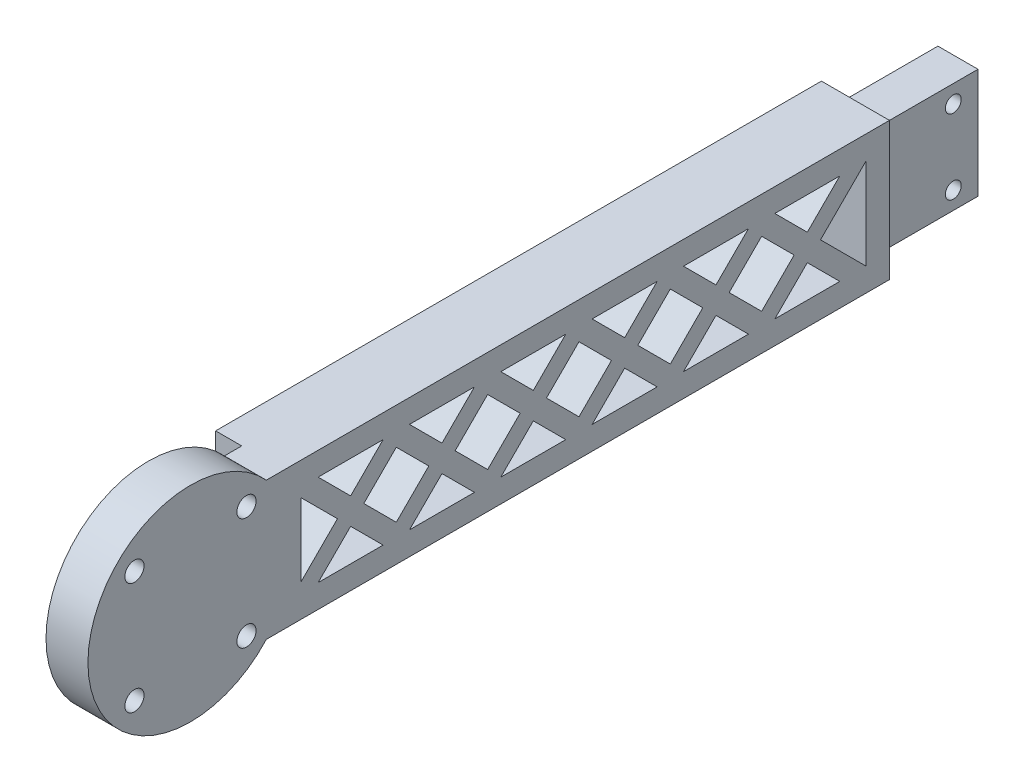
SolidWorks part; units mm, degrees
ref_plane "Front Plane" through (0, 0, 0) normal (1, 0, 0) x (0, 1, 0)
ref_plane "Top Plane" through (0, 0, 0) normal (0, 0, 1) x (0, 1, 0)
ref_plane "Right Plane" through (0, 0, 0) normal (0, 1, 0) x (-1, 0, 0)
sketch "Sketch1" plane through (0, 0, 0) normal (0, 0, 1) x (0, 1, 0)
  line L1 (-12.9849, 6.6346) -> (10.6151, 6.6346)
  line L2 (-12.9849, 6.6346) -> (-12.9849, -1.9654)
  line L3 (-12.9849, -1.9654) -> (10.6151, -1.9654)
  line L4 (10.6151, 6.6346) -> (10.6151, -1.9654)
  dimension "D1" = 23.6
  dimension "D2" = 8.6
extrude "Boss-Extrude1" add sketch "Sketch1" along normal blind 22
sketch "Sketch2" plane through (0, 0, 22) normal (0, 0, 1) x (1, 0, 0)
  line L0 (1.9654, 10.6151) -> (-6.6346, 10.6151) construction
  line L1 (-9.6346, 13.6151) -> (4.9654, 13.6151)
  line L2 (-9.6346, 13.6151) -> (-9.6346, -15.9849)
  line L3 (-9.6346, -15.9849) -> (4.9654, -15.9849)
  line L4 (4.9654, 13.6151) -> (4.9654, -15.9849)
  line L5 (1.9654, -12.9849) -> (1.9654, 10.6151) construction
  line L6 (-6.6346, 10.6151) -> (-6.6346, -12.9849) construction
  line L7 (-6.6346, -12.9849) -> (1.9654, -12.9849) construction
  dimension "D1" = 3
  dimension "D2" = 3
  dimension "D3" = 3
  dimension "D4" = 3
extrude "Boss-Extrude2" add sketch "Sketch2" along normal blind 130 contours L2 L3 L4 L1
sketch "Sketch3" plane through (1.9654, 0, 0) normal (1, 0, 0) x (0, 1, 0)
  line L0 (-12.9849, 0) -> (10.6151, 0) construction
  line L1 (-9.1849, 5.3) -> (6.8151, 5.3) construction
  line L2 (-9.1849, 5.3) -> (-12.9849, 5.3) construction
  line L3 (-12.9849, 22) -> (-12.9849, 0) construction
  line L4 (6.8151, 5.3) -> (10.6151, 5.3) construction
  line L5 (10.6151, 22) -> (10.6151, 0) construction
  circle A0 centre (6.8151, 5.3) radius 1.7
  circle A1 centre (-9.1849, 5.3) radius 1.7
  dimension "D1" = 5.3
  dimension "D2" = 3.4
  dimension "D3" = 3.4
  dimension "D4" = 16
extrude "Cut-Extrude1" cut sketch "Sketch3" against normal blind 9
sketch "Sketch4" plane through (4.9654, 0, 0) normal (1, 0, 0) x (0, 1, 0)
  line L0 (13.6151, 152) -> (13.6151, 22) construction
  line L1 (-15.9849, 127) -> (13.6151, 127)
  line L2 (-15.9849, 127) -> (-15.9849, 27)
  line L3 (-15.9849, 27) -> (13.6151, 27)
  line L4 (13.6151, 127) -> (13.6151, 27)
  line L5 (-10.9849, 127) -> (-10.9849, 27)
  line L6 (8.6151, 127) -> (8.6151, 27)
  line L7 (13.6151, 22) -> (-15.9849, 22) construction
  line L8 (8.6151, 32.6569) -> (-10.9849, 52.2569)
  line L9 (-10.9849, 27) -> (8.6151, 46.6)
  line L10 (8.6151, 27) -> (-10.9849, 46.6)
  line L11 (-10.9849, 46.6) -> (8.6151, 66.2)
  line L12 (8.6151, 66.2) -> (-10.9849, 85.8)
  line L13 (-10.9849, 85.8) -> (8.6151, 105.4)
  line L14 (8.6151, 46.6) -> (-10.9849, 66.2)
  line L15 (-10.9849, 66.2) -> (8.6151, 85.8)
  line L16 (8.6151, 85.8) -> (-10.9849, 105.4)
  line L17 (-15.9849, 152) -> (-15.9849, 22) construction
  line L18 (-10.9849, 105.4) -> (8.6151, 125)
  line L19 (8.6151, 105.4) -> (-10.9849, 125)
  line L20 (-10.9849, 32.6569) -> (8.6151, 52.2569)
  line L21 (-10.9849, 52.2569) -> (8.6151, 71.8569)
  line L22 (8.6151, 52.2569) -> (-10.9849, 71.8569)
  line L23 (-10.9849, 71.8569) -> (8.6151, 91.4569)
  line L24 (8.6151, 71.8569) -> (-10.9849, 91.4569)
  line L25 (-10.9849, 91.4569) -> (8.6151, 111.0569)
  line L26 (8.6151, 91.4569) -> (-10.9849, 111.0569)
  line L27 (-10.9849, 111.0569) -> (4.9583, 127)
  line L28 (8.6151, 111.0569) -> (-7.328, 127)
  line L29 (-10.9849, 127) -> (-10.9849, 152)
  line L30 (13.6151, 152) -> (-15.9849, 152) construction
  line L31 (8.6151, 127) -> (8.6151, 152)
  line L32 (-7.328, 127) -> (-10.9849, 130.6569)
  line L33 (4.9583, 127) -> (8.6151, 130.6569)
  line L34 (-10.9849, 130.6569) -> (8.6151, 150.2569)
  line L35 (-10.9849, 125) -> (8.6151, 144.6)
  line L36 (8.6151, 130.6569) -> (-10.9849, 150.2569)
  line L37 (8.6151, 125) -> (-10.9849, 144.6)
  line L38 (-10.9849, 148.2569) -> (8.6151, 148.2569)
  dimension "D1" = 100
  dimension "D2" = 5
  dimension "D3" = 5
  dimension "D4" = 5
  dimension "D5" = 4
  dimension "D6" = 4
  dimension "D7" = 2
extrude "Cut-Extrude2" cut sketch "Sketch4" against normal blind 19 and the other way through all contours L5 L27 L19 | L28 L27 L1 | L28 L6 L18 | L26 L25 L19 L18 | L5 L25 L16 | L26 L6 L13 | L24 L23 L16 L13 | L5 L23 L12 | L24 L6 L15 | L22 L21 L12 L15 | L5 L21 L14 | L22 L6 L11 | L8 L20 L14 L11 | L5 L20 L10 | L9 L8 L6 | L3 L10 L9 | L33 L37 L35 L32 L1 | L34 L37 L29 | L38 L36 L34 | L36 L31 L35
sketch "Sketch5" plane through (4.9654, 0, 0) normal (1, 0, 0) x (0, 1, 0)
  line L0 (-1.1849, 172) -> (-1.1849, 152) construction
  line L1 (13.6151, 152) -> (-15.9849, 152) construction
  line L2 (-1.1849, 172) -> (-1.1849, 189) construction
  line L3 (-15.9849, 152) -> (-15.9849, 155.7224)
  line L4 (13.6151, 152) -> (13.6151, 155.7224)
  line L5 (-15.9849, 152) -> (-10.35, 152)
  line L6 (13.6151, 152) -> (7.9803, 152)
  line L7 (-1.1849, 172) -> (-13.2057, 184.0208) construction
  circle A0 centre (-1.1849, 172) radius 22
  circle A1 centre (-13.2057, 184.0208) radius 2.06
  circle A2 centre (10.8359, 184.0208) radius 2.06
  circle A3 centre (10.8359, 159.9792) radius 2.06
  circle A4 centre (-13.2057, 159.9792) radius 2.06
  point P8 (-1.1849, 152)
  dimension "D1" = 44
  dimension "D3" = 17
  dimension "D4" = 45
  dimension "D5" = 4.12
  dimension "D2" = 20
  dimension "D6" = 4
extrude "Boss-Extrude3" add sketch "Sketch5" against normal blind 9
